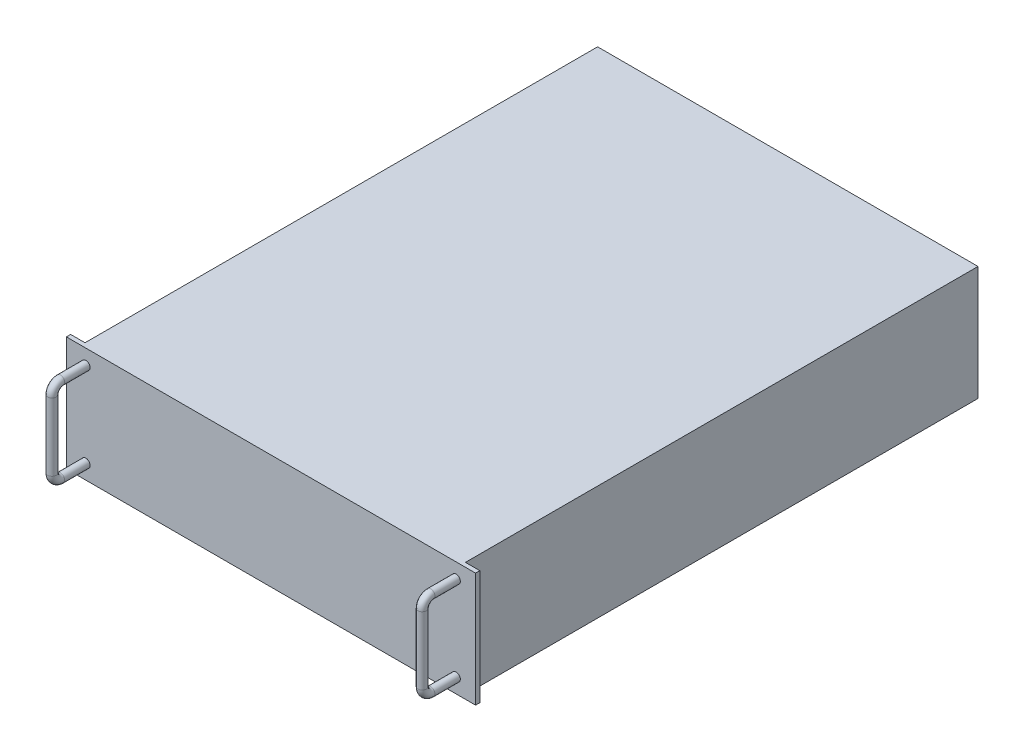
SolidWorks part; units mm, degrees
material "PVC Rigid"
ref_plane "Front Plane" through (0, 0, 0) normal (0, 0, 1) x (1, 0, 0)
ref_plane "Top Plane" through (0, 0, 0) normal (0, 1, 0) x (1, 0, 0)
ref_plane "Right Plane" through (0, 0, 0) normal (1, 0, 0) x (0, 0, -1)
sketch "Sketch1" plane through (0, 0, 0) normal (0, 0, 1) x (1, 0, 0)
  line L1 (0, 0) -> (483, 0)
  line L2 (0, 0) -> (0, 135)
  line L3 (0, 135) -> (483, 135)
  line L4 (483, 0) -> (483, 135)
  dimension "D1" = 135
  dimension "D2" = 483
extrude "Boss-Extrude1" add sketch "Sketch1" against normal blind 610
sketch "Sketch2" plane through (0, 0, -610) normal (0, 0, -1) x (-1, 0, 0)
  line L0 (0, 0) -> (-483, 0) construction
  line L1 (-483, 135) -> (-466, 135)
  line L2 (-483, 135) -> (-483, 0)
  line L3 (-483, 0) -> (-466, 0)
  line L4 (-466, 135) -> (-466, 0)
  line L5 (-483, 135) -> (0, 135) construction
  line L6 (0, 0) -> (-17, 0)
  line L7 (0, 0) -> (0, 135)
  line L8 (0, 135) -> (-17, 135)
  line L9 (-17, 0) -> (-17, 135)
  dimension "D1" = 17
  dimension "D2" = 17
extrude "Cut-Extrude1" cut sketch "Sketch2" against normal blind 605
ref_plane "Plane1" through (460, 0, 0) normal (1, 0, 0) x (0, 0, -1)
sketch "Sketch3" plane through (460, 0, 0) normal (1, 0, 0) x (0, 0, -1)
  line L0 (0, 117.5) -> (-30, 117.5)
  line L1 (0, 0) -> (0, 135) construction
  line L2 (-40, 107.5) -> (-40, 27.5)
  line L3 (-30, 17.5) -> (0, 17.5)
  line L4 (5, 0) -> (610, 0) construction
  arc A0 (-30, 17.5) -> (-40, 27.5) centre (-30, 27.5) cw
  arc A1 (-40, 107.5) -> (-30, 117.5) centre (-30, 107.5) cw
  point P12 (-40, 17.5)
  point P15 (-40, 117.5)
  dimension "D4" = 10
  dimension "D1" = 100
  dimension "D2" = 40
  dimension "D3" = 17.5
sketch "Sketch4" plane through (0, 0, 0) normal (0, 0, 1) x (1, 0, 0)
  line L0 (460, 107.5) -> (460, 27.5) construction
  line L1 (460, -74.25) -> (460, 74.25) construction
  circle A0 centre (460, 117.5) radius 5
  dimension "D1" = 10
sweep "Sweep1" add profiles "Sketch4" path "Sketch3"
ref_plane "Plane2" through (241.5, 0, 0) normal (1, 0, 0) x (0, 0, -1)
mirror "Mirror1" about plane through (241.5, 0, 0) normal (1, 0, 0) of "Sweep1"
